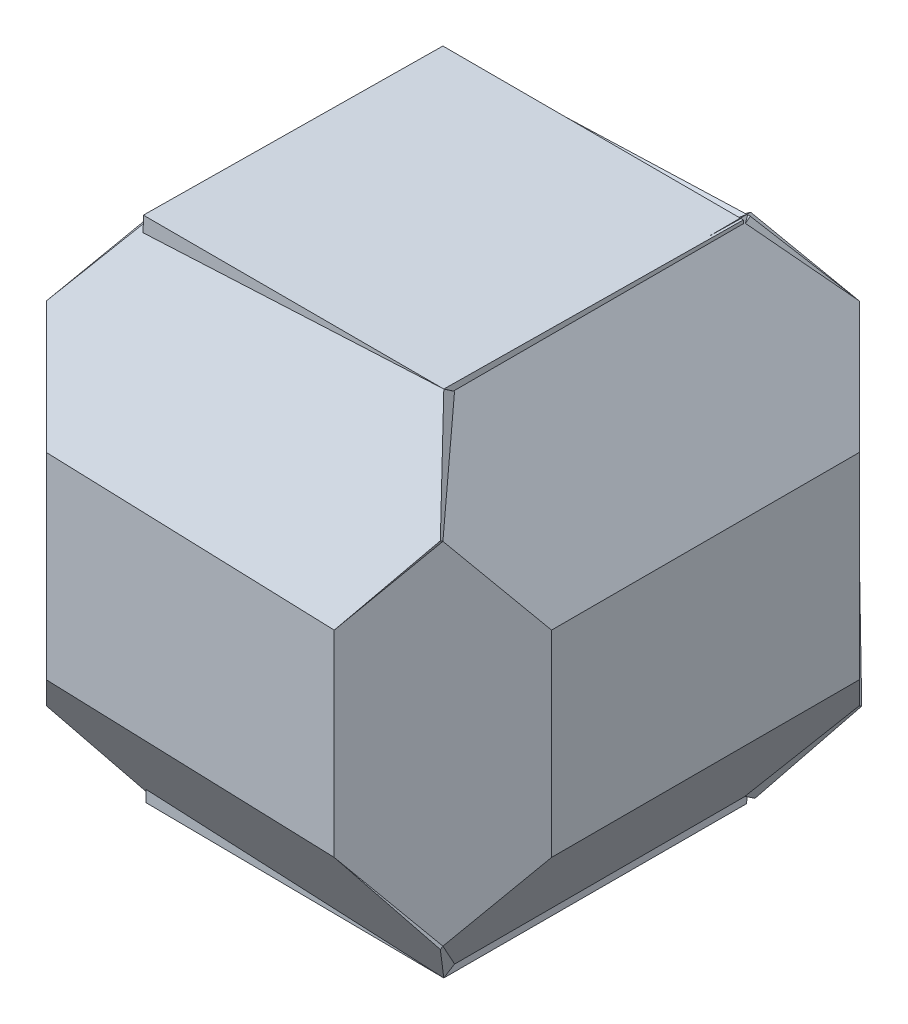
SolidWorks part; units mm, degrees
ref_plane "Front Plane" through (0, 0, 0) normal (0, 0, 1) x (1, 0, 0)
ref_plane "Top Plane" through (0, 0, 0) normal (0, 1, 0) x (1, 0, 0)
ref_plane "Right Plane" through (0, 0, 0) normal (1, 0, 0) x (0, 0, -1)
sketch "Sketch1" plane through (0, 0, 0) normal (0, 0, 1) x (1, 0, 0)
  line L1 (0, 0) -> (50, 0)
  line L2 (0, 0) -> (0, 50)
  line L3 (0, 50) -> (50, 50)
  line L4 (50, 0) -> (50, 50)
extrude "Boss-Extrude1" add sketch "Sketch1" along normal blind 50
ref_plane "Plane1" through (25, 0, 25) normal (-0.7071, 0, -0.7071) x (-0.7071, 0, 0.7071)
ref_plane "Plane2" through (-3.2843, 0, -3.2843) normal (-0.7071, 0, -0.7071) x (-0.7071, 0, 0.7071)
sketch "Sketch7" plane through (-3.2843, 0, -3.2843) normal (-0.7071, 0, -0.7071) x (-0.7071, 0, 0.7071)
  line L1 (0, 50) -> (0, 0) construction
  line L2 (0, 50) -> (-10.9602, 39.0398)
  line L3 (-10.9602, 39.0398) -> (-10.9602, 10.9602)
  line L4 (-10.9602, 10.9602) -> (0, 0)
  line L6 (10.9602, 10.9602) -> (0, 0)
  line L7 (10.9602, 39.0398) -> (10.9602, 10.9602)
  line L8 (0, 50) -> (10.9602, 39.0398)
  dimension "D1" = 45
  dimension "D2" = 45
  dimension "D3" = 15.5
extrude "Boss-Extrude2" add sketch "Sketch7" against normal blind 82
ref_plane "Plane4" through (0, 0, 0) normal (-0.7071, 0, 0.7071) x (0.7071, 0, 0.7071)
ref_plane "Plane5" through (-28.2843, 0, 28.2843) normal (-0.7071, 0, 0.7071) x (0.7071, 0, 0.7071)
sketch "Sketch9" plane through (-28.2843, 0, 28.2843) normal (-0.7071, 0, 0.7071) x (0.7071, 0, 0.7071)
  line L0 (35.3553, 50) -> (35.3553, 0) construction
  line L1 (35.3553, 50) -> (35.3553, 0)
  line L2 (35.3553, 0) -> (46.3155, 10.9602)
  line L3 (35.3553, 0) -> (24.3952, 10.9602)
  line L4 (35.3553, 25) -> (24.3952, 25) construction
  line L5 (35.3553, 50) -> (46.3155, 39.0398)
  line L6 (35.3553, 50) -> (24.3952, 39.0398)
  line L7 (46.3155, 39.0398) -> (46.3155, 10.9602)
  line L8 (24.3952, 10.9602) -> (24.3952, 39.0398)
  dimension "D1" = 15.5
  dimension "D2" = 15.5
  dimension "D3" = 45
  dimension "D4" = 45
extrude "Boss-Extrude3" add sketch "Sketch9" against normal blind 82 contours L7 L5 L1 L2 | L1 L4 L8 L3 | L4 L1 L6 L8
ref_plane "Plane6" through (62.4485, 0, 0) normal (1, 0, 0) x (0, 0, -1)
sketch "Sketch10" plane through (62.4485, 0, 0) normal (1, 0, 0) x (0, 0, -1)
  line L1 (-3.0515, 39.0398) -> (-46.9485, 39.0398)
  line L2 (-3.0515, 39.0398) -> (-3.0515, 10.9602)
  line L3 (-3.0515, 10.9602) -> (-46.9485, 10.9602)
  line L4 (-46.9485, 39.0398) -> (-46.9485, 10.9602)
extrude "Boss-Extrude4" add sketch "Sketch10" against normal blind 67
ref_plane "Plane7" through (-11.0343, 0, 0) normal (-1, 0, 0) x (0, 0, 1)
sketch "Sketch11" plane through (-11.0343, 0, 0) normal (-1, 0, 0) x (0, 0, 1)
  line L1 (4.4657, 10.9602) -> (45.5343, 10.9602)
  line L2 (4.4657, 10.9602) -> (4.4657, 39.0398)
  line L3 (4.4657, 39.0398) -> (45.5343, 39.0398)
  line L4 (45.5343, 10.9602) -> (45.5343, 39.0398)
extrude "Boss-Extrude5" add sketch "Sketch11" against normal blind 69
ref_plane "Plane8" through (-0.362, 0, -10.8736) normal (0.0333, 0, 0.9994) x (0.9994, 0, -0.0333)
sketch "Sketch12" plane through (-0.362, 0, -10.8736) normal (0.0333, 0, 0.9994) x (0.9994, 0, -0.0333)
  line L1 (4.8304, 39.0398) -> (47.3367, 39.0398)
  line L2 (4.8304, 39.0398) -> (4.8304, 10.9602)
  line L3 (4.8304, 10.9602) -> (47.3367, 10.9602)
  line L4 (47.3367, 39.0398) -> (47.3367, 10.9602)
extrude "Boss-Extrude6" add sketch "Sketch12" along normal blind 69
ref_plane "Plane9" through (-2.0246, 0, 60.8182) normal (0.0333, 0, -0.9994) x (-0.9994, 0, -0.0333)
sketch "Sketch13" plane through (-2.0246, 0, 60.8182) normal (0.0333, 0, -0.9994) x (-0.9994, 0, -0.0333)
  line L1 (-6.4939, 39.0398) -> (-49.0002, 39.0398)
  line L2 (-6.4939, 39.0398) -> (-6.4939, 10.9602)
  line L3 (-6.4939, 10.9602) -> (-49.0002, 10.9602)
  line L4 (-49.0002, 39.0398) -> (-49.0002, 10.9602)
extrude "Boss-Extrude7" add sketch "Sketch13" along normal blind 69
ref_plane "Plane10" through (0, 0, 0) normal (0.7071, -0.7071, 0) x (-0.7071, -0.7071, 0)
ref_plane "Plane13" through (-1.2105, -24.8562, 36.3624) normal (0.0275, 0.5641, -0.8252) x (-0.9996, 0.0155, -0.0227)
sketch "Sketch18" plane through (-1.2105, -24.8562, 36.3624) normal (0.0275, 0.5641, -0.8252) x (-0.9996, 0.0155, -0.0227)
  line L0 (-5.6783, 43.4912) -> (2.0746, 30.0695)
  line L1 (-5.6783, 43.4912) -> (-48.1771, 44.2893)
  line L2 (-48.1771, 44.2893) -> (-55.9184, 30.8676)
  line L3 (-55.9184, 30.8676) -> (2.0746, 30.0695)
  line L4 (-48.5494, 17.2379) -> (-55.9184, 30.8676)
  line L5 (-6.0447, 16.8662) -> (2.0746, 30.0695)
  line L6 (-6.0447, 16.8662) -> (-48.5494, 17.2379)
extrude "Boss-Extrude11" add sketch "Sketch18" along normal blind 35 contours L2 L3 L0 L1 | L6 L5 L3 L4
ref_plane "Plane14" through (-0.0769, -1.5798, -2.3111) normal (0.0275, 0.5641, 0.8252) x (0.9996, -0.0155, -0.0227)
sketch "Sketch20" plane through (-0.0769, -1.5798, -2.3111) normal (0.0275, 0.5641, 0.8252) x (0.9996, -0.0155, -0.0227)
  line L0 (4.5444, 15.2751) -> (-3.2085, 1.8534) construction
  line L1 (4.5444, 15.2751) -> (47.0432, 16.0732) construction
  line L2 (4.5444, 15.2751) -> (-3.2085, 1.8534)
  line L3 (4.5444, 15.2751) -> (47.0432, 16.0732)
  line L4 (54.7844, 2.6515) -> (47.0432, 16.0732) construction
  line L5 (54.7844, 2.6515) -> (47.0432, 16.0732)
  line L6 (54.7844, 2.6515) -> (-3.2085, 1.8534)
  line L7 (54.7844, 2.6515) -> (47.4154, -10.9782)
  line L8 (4.9108, -11.3499) -> (47.4154, -10.9782)
  line L9 (4.9108, -11.3499) -> (-3.2085, 1.8534)
extrude "Boss-Extrude12" add sketch "Sketch20" along normal blind 20 contours L9 L8 L7 L6 | L6 L5 L3 L2
ref_plane "Plane15" through (-2.1895, -1.5482, 0) normal (-0.8165, -0.5774, 0) x (0, 0, 1)
sketch "Sketch21" plane through (-2.1895, -1.5482, 0) normal (-0.8165, -0.5774, 0) x (0, 0, 1)
  line L0 (53.2843, 1.8962) -> (45.5343, 15.3196) construction
  line L1 (4.4657, 15.3196) -> (45.5343, 15.3196) construction
  line L2 (4.4657, 15.3196) -> (-3.2843, 1.8962) construction
  line L3 (53.2843, 1.8962) -> (45.5343, 15.3196)
  line L4 (4.4657, 15.3196) -> (45.5343, 15.3196)
  line L5 (4.4657, 15.3196) -> (-3.2843, 1.8962)
  line L6 (-3.2843, 1.8962) -> (53.2843, 1.8962)
  line L7 (4.4657, -11.5272) -> (-3.2843, 1.8962)
  line L8 (53.2843, 1.8962) -> (45.5343, -11.5272)
  line L9 (4.4657, -11.5272) -> (45.5343, -11.5272)
extrude "Boss-Extrude13" add sketch "Sketch21" against normal blind 35 contours L5 L6 L3 L4 | L7 L9 L8 L6
ref_plane "Plane16" through (-0.091, -10.9851, 0) normal (0.0083, 1, 0) x (1, -0.0083, 0)
ref_plane "Plane17" through (-0.091, -10.9851, 0) normal (-0.0083, -1, 0) x (-1, 0.0083, 0)
ref_plane "Plane18" through (36.4657, -25.7851, 0) normal (0.8165, -0.5774, 0) x (0, 0, -1)
sketch "Sketch24" plane through (36.4657, -25.7851, 0) normal (0.8165, -0.5774, 0) x (0, 0, -1)
  line L0 (4.6985, 31.5802) -> (-3.0515, 45.0036) construction
  line L1 (-46.9485, 45.0036) -> (-3.0515, 45.0036) construction
  line L2 (-46.9485, 45.0036) -> (-54.6985, 31.5802) construction
  line L3 (4.6985, 31.5802) -> (-3.0515, 45.0036)
  line L4 (-46.9485, 45.0036) -> (-3.0515, 45.0036)
  line L5 (-46.9485, 45.0036) -> (-54.6985, 31.5802)
  line L6 (-54.6985, 31.5802) -> (4.6985, 31.5802)
  line L7 (-46.9485, 18.1568) -> (-54.6985, 31.5802)
  line L8 (-46.9485, 18.1568) -> (-3.0515, 18.1568)
  line L9 (4.6985, 31.5802) -> (-3.0515, 18.1568)
extrude "Boss-Extrude16" add sketch "Sketch24" against normal blind 30 contours L5 L6 L3 L4 | L9 L6 L7 L8
ref_plane "Plane19" through (-0.8547, 18.7593, -25.675) normal (-0.0269, 0.5897, -0.8071) x (-0.9996, -0.0159, 0.0217)
sketch "Sketch25" plane through (-0.8547, 18.7593, -25.675) normal (-0.0269, 0.5897, -0.8071) x (-0.9996, -0.0159, 0.0217)
  line L0 (-55.5732, 37.6001) -> (-47.8204, 24.1783) construction
  line L1 (-47.8204, 24.1783) -> (-5.3223, 25.0126) construction
  line L2 (2.4193, 38.4344) -> (-5.3223, 25.0126) construction
  line L3 (-55.5732, 37.6001) -> (-47.8204, 24.1783)
  line L4 (-47.8204, 24.1783) -> (-5.3223, 25.0126)
  line L5 (2.4193, 38.4344) -> (-5.3223, 25.0126)
  line L6 (2.4193, 38.4344) -> (-55.5732, 37.6001)
  line L7 (2.4193, 38.4344) -> (-5.7053, 51.6279)
  line L8 (-48.2098, 51.2393) -> (-5.7053, 51.6279)
  line L9 (-55.5732, 37.6001) -> (-48.2098, 51.2393)
extrude "Boss-Extrude17" add sketch "Sketch25" against normal blind 30 contours L9 L6 L7 L8 | L5 L6 L3 L4
ref_plane "Plane20" through (-25.7597, 18.2149, 0) normal (0.8165, -0.5774, 0) x (0, 0, -1)
sketch "Sketch26" plane through (-25.7597, 18.2149, 0) normal (0.8165, -0.5774, 0) x (0, 0, -1)
  line L0 (3.2843, 38.9287) -> (-4.4657, 25.5053) construction
  line L1 (-45.5343, 25.5053) -> (-4.4657, 25.5053) construction
  line L2 (-53.2843, 38.9287) -> (-45.5343, 25.5053) construction
  line L3 (3.2843, 38.9287) -> (-4.4657, 25.5053)
  line L4 (-45.5343, 25.5053) -> (-4.4657, 25.5053)
  line L5 (-53.2843, 38.9287) -> (-45.5343, 25.5053)
  line L6 (-53.2843, 38.9287) -> (3.2843, 38.9287)
  line L7 (-53.2843, 38.9287) -> (-45.5343, 52.352)
  line L8 (-45.5343, 52.352) -> (-4.4657, 52.352)
  line L9 (3.2843, 38.9287) -> (-4.4657, 52.352)
extrude "Boss-Extrude18" add sketch "Sketch26" along normal blind 30 contours L6 L9 L8 L7 | L6 L5 L4 L3
ref_plane "Plane21" through (-1.9853, 40.7672, 59.6388) normal (0.0275, -0.5641, -0.8252) x (-0.9996, -0.0155, -0.0227)
sketch "Sketch27" plane through (-1.9853, 40.7672, 59.6388) normal (0.0275, -0.5641, -0.8252) x (-0.9996, -0.0155, -0.0227)
  line L0 (-6.4535, -2.2135) -> (-48.9523, -3.0116) construction
  line L1 (1.2994, 11.2082) -> (-6.4535, -2.2135) construction
  line L2 (-56.6935, 10.4101) -> (-48.9523, -3.0116) construction
  line L3 (-6.4535, -2.2135) -> (-48.9523, -3.0116)
  line L4 (1.2994, 11.2082) -> (-6.4535, -2.2135)
  line L5 (-56.6935, 10.4101) -> (-48.9523, -3.0116)
  line L6 (1.2994, 11.2082) -> (-56.6935, 10.4101)
  line L7 (-56.6935, 10.4101) -> (-49.3246, 24.0398)
  line L8 (-6.8199, 24.4115) -> (-49.3246, 24.0398)
  line L9 (1.2994, 11.2082) -> (-6.8199, 24.4115)
extrude "Boss-Extrude19" add sketch "Sketch27" along normal blind 30 contours L4 L6 L5 L3 | L6 L9 L8 L7
ref_plane "Plane22" through (60.0359, 42.4518, 0) normal (0.8165, 0.5774, 0) x (0, 0, -1)
sketch "Sketch28" plane through (60.0359, 42.4518, 0) normal (0.8165, 0.5774, 0) x (0, 0, -1)
  line L0 (-3.0515, -4.1787) -> (-46.9485, -4.1787) construction
  line L1 (-54.6985, 9.2446) -> (-46.9485, -4.1787) construction
  line L2 (4.6985, 9.2446) -> (-3.0515, -4.1787) construction
  line L3 (-3.0515, -4.1787) -> (-46.9485, -4.1787)
  line L4 (-54.6985, 9.2446) -> (-46.9485, -4.1787)
  line L5 (4.6985, 9.2446) -> (-3.0515, -4.1787)
  line L6 (-54.6985, 9.2446) -> (4.6985, 9.2446)
  line L7 (4.6985, 9.2446) -> (-3.0515, 22.668)
  line L8 (-54.6985, 9.2446) -> (-46.9485, 22.668)
  line L9 (-3.0515, 22.668) -> (-46.9485, 22.668)
extrude "Boss-Extrude20" add sketch "Sketch28" against normal blind 30 contours L6 L4 L3 L5 | L7 L9 L8 L6
ref_plane "Plane23" through (0.0759, 60.909, -0.6718) normal (0.0012, 0.9999, -0.011) x (1, -0.0012, 0)
sketch "Sketch30" plane through (0.0759, 60.909, -0.6718) normal (0.0012, 0.9999, -0.011) x (1, -0.0012, 0)
  line L1 (4.3898, -5.1378) -> (47.2447, -5.1378)
  line L2 (4.3898, -5.1378) -> (4.3898, -47.8653)
  line L3 (4.3898, -47.8653) -> (47.2447, -47.8653)
  line L4 (47.2447, -5.1378) -> (47.2447, -47.8653)
extrude "Boss-Extrude21" add sketch "Sketch30" against normal blind 40
ref_plane "Plane25" through (-0.1077, -10.9834, 0.0164) normal (-0.0098, -1, 0.0015) x (-1, 0.0098, 0)
sketch "Sketch32" plane through (-0.1077, -10.9834, 0.0164) normal (-0.0098, -1, 0.0015) x (-1, 0.0098, 0)
  line L0 (-47.0544, -46.5575) -> (-47.0538, -3.4097) construction
  line L1 (-4.9399, -3.966) -> (-47.43, -2.7917) construction
  line L2 (-4.5731, -4.4493) -> (-4.5737, -45.5178) construction
  line L3 (-47.0544, -46.5575) -> (-47.0538, -3.4097)
  line L4 (-4.9399, -3.966) -> (-47.43, -2.7917)
  line L5 (-4.5731, -4.4493) -> (-4.5737, -45.5178)
  line L13 (-31.4474, -30.2917) -> (-47.0544, -46.5575)
  line L14 (-47.0544, -46.5575) -> (-47.47, -45.6924)
  line L15 (-47.47, -45.6924) -> (-47.4306, -47.1742)
  line L16 (-47.4306, -47.1742) -> (-4.9406, -46.001)
  line L17 (-4.9406, -46.001) -> (-4.9536, -45.5095)
  line L18 (-4.9536, -45.5095) -> (-19.9652, -30.1137)
  line L19 (-19.9652, -30.1137) -> (-31.4474, -30.2917)
  line L20 (-31.4474, -30.2917) -> (-47.0544, -46.5575)
  line L21 (-47.0544, -46.5575) -> (-47.47, -45.6924)
  line L22 (-47.47, -45.6924) -> (-47.4306, -47.1742)
  line L23 (-47.4306, -47.1742) -> (-4.9406, -46.001)
  line L24 (-4.9406, -46.001) -> (-4.9536, -45.5095)
  line L25 (-4.9536, -45.5095) -> (-19.9652, -30.1137)
  line L26 (-19.9652, -30.1137) -> (-31.4474, -30.2917)
  dimension "D1" = 0
sketch "Sketch33" plane through (-0.1077, -10.9834, 0.0164) normal (-0.0098, -1, 0.0015) x (-1, 0.0098, 0)
  line L1 (-47.4306, -47.1742) -> (-4.9399, -47.1742)
  line L2 (-47.4306, -47.1742) -> (-47.4306, -3.966)
  line L3 (-47.4306, -3.966) -> (-4.9399, -3.966)
  line L4 (-4.9399, -47.1742) -> (-4.9399, -3.966)
extrude "Boss-Extrude23" add sketch "Sketch33" against normal blind 40
